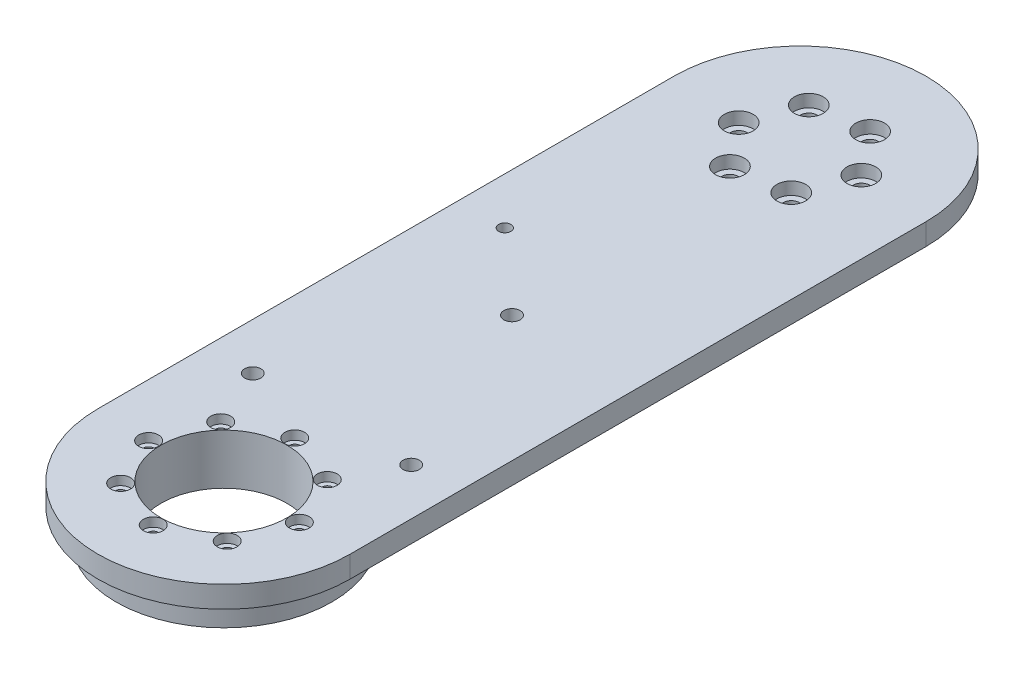
SolidWorks part; units mm, degrees
material "Aleación 6061"
ref_plane "Alzado" through (0, 0, 0) normal (0, 0, 1) x (1, 0, 0)
ref_plane "Planta" through (0, 0, 0) normal (0, 1, 0) x (1, 0, 0)
ref_plane "Vista lateral" through (0, 0, 0) normal (1, 0, 0) x (0, 0, -1)
sketch "Sk_Placa" plane through (0, 0, 0) normal (0, 1, 0) x (1, 0, 0)
  line L1 (-35, -330) -> (35, -330)
  line L2 (-35, -330) -> (-35, -170)
  line L3 (-35, -170) -> (35, -170)
  line L4 (35, -330) -> (35, -170)
  line L5 (-35, -330) -> (35, -170) construction
  line L6 (-35, -170) -> (35, -330) construction
  point P0 (0, -250)
  dimension "D1" = 70
  dimension "D2" = 160
  dimension "D3" = 250
extrude "Placa" add sketch "Sk_Placa" along normal blind 6 from offset 46.75
sketch "Sk_Extremos" plane through (0, 0, 0) normal (0, 1, 0) x (1, 0, 0)
  circle A0 centre (0, -170) radius 35
  circle A1 centre (0, -330) radius 35
  dimension "D1" = 70
  dimension "D3" = 70
  dimension "D2" = 170
  dimension "D4" = 330
extrude "Extremos" add sketch "Sk_Extremos" along normal blind 6 from offset 46.75
sketch "Sk_Pasantes_M4_separadores" plane through (0, 0, 0) normal (0, 1, 0) x (1, 0, 0)
  circle A0 centre (0, -250) radius 2.25
  circle A1 centre (-22, -300) radius 2.25
  circle A2 centre (22, -300) radius 2.25
  dimension "D1" = 4.5
  dimension "D3" = 4.5
  dimension "D6" = 4.5
  dimension "D2" = 250
  dimension "D4" = 22
  dimension "D5" = 300
  dimension "D7" = 22
  dimension "D8" = 300
extrude "Pasantes_M4_separadores" cut sketch "Sk_Pasantes_M4_separadores" along normal blind 6 from offset 46.75
sketch "Sk_Asiento_J3" plane through (0, 0, 0) normal (0, 1, 0) x (1, 0, 0)
  circle A0 centre (0, -330) radius 30
  circle A1 centre (0, -330) radius 17.5
  dimension "D1" = 60
  dimension "D3" = 35
  dimension "D2" = 330
  dimension "D4" = 330
extrude "Asiento_J3" add sketch "Sk_Asiento_J3" along normal blind 8 from offset 38.75
sketch "Sk_Paso_rotor_J3" plane through (0, 0, 0) normal (0, 1, 0) x (1, 0, 0)
  circle A0 centre (0, -330) radius 17.5
  dimension "D1" = 35
  dimension "D2" = 330
extrude "Paso_rotor_J3" cut sketch "Sk_Paso_rotor_J3" along normal blind 14 from offset 38.75
sketch "Sk_Pasantes_M2-5_estator_J3" plane through (0, 0, 0) normal (0, 1, 0) x (1, 0, 0)
  circle A0 centre (20.29, -329.3624) radius 1.45
  circle A1 centre (14.7981, -343.8963) radius 1.45
  circle A2 centre (0.6376, -350.29) radius 1.45
  circle A3 centre (-13.8963, -344.7981) radius 1.45
  circle A4 centre (-20.29, -330.6376) radius 1.45
  circle A5 centre (-14.7981, -316.1037) radius 1.45
  circle A6 centre (-0.6376, -309.71) radius 1.45
  circle A7 centre (13.8963, -315.2019) radius 1.45
  dimension "D1" = 2.9
  dimension "D4" = 2.9
  dimension "D7" = 2.9
  dimension "D10" = 2.9
  dimension "D13" = 2.9
  dimension "D16" = 2.9
  dimension "D19" = 2.9
  dimension "D22" = 2.9
  dimension "D2" = 20.29
  dimension "D3" = 329.3624
  dimension "D5" = 14.7981
  dimension "D6" = 343.8963
  dimension "D8" = 0.6376
  dimension "D9" = 350.29
  dimension "D11" = 13.8963
  dimension "D12" = 344.7981
  dimension "D14" = 20.29
  dimension "D15" = 330.6376
  dimension "D17" = 14.7981
  dimension "D18" = 316.1037
  dimension "D20" = 0.6376
  dimension "D21" = 309.71
  dimension "D23" = 13.8963
  dimension "D24" = 315.2019
extrude "Pasantes_M2-5_estator_J3" cut sketch "Sk_Pasantes_M2-5_estator_J3" along normal blind 14 from offset 38.75
sketch "Sk_Cajas_M2-5_J3" plane through (0, 0, 0) normal (0, 1, 0) x (1, 0, 0)
  circle A0 centre (20.29, -329.3624) radius 2.75
  circle A1 centre (14.7981, -343.8963) radius 2.75
  circle A2 centre (0.6376, -350.29) radius 2.75
  circle A3 centre (-13.8963, -344.7981) radius 2.75
  circle A4 centre (-20.29, -330.6376) radius 2.75
  circle A5 centre (-14.7981, -316.1037) radius 2.75
  circle A6 centre (-0.6376, -309.71) radius 2.75
  circle A7 centre (13.8963, -315.2019) radius 2.75
  dimension "D1" = 5.5
  dimension "D4" = 5.5
  dimension "D7" = 5.5
  dimension "D10" = 5.5
  dimension "D13" = 5.5
  dimension "D16" = 5.5
  dimension "D19" = 5.5
  dimension "D22" = 5.5
  dimension "D2" = 20.29
  dimension "D3" = 329.3624
  dimension "D5" = 14.7981
  dimension "D6" = 343.8963
  dimension "D8" = 0.6376
  dimension "D9" = 350.29
  dimension "D11" = 13.8963
  dimension "D12" = 344.7981
  dimension "D14" = 20.29
  dimension "D15" = 330.6376
  dimension "D17" = 14.7981
  dimension "D18" = 316.1037
  dimension "D20" = 0.6376
  dimension "D21" = 309.71
  dimension "D23" = 13.8963
  dimension "D24" = 315.2019
extrude "Cajas_M2-5_J3" cut sketch "Sk_Cajas_M2-5_J3" along normal blind 2.5 from offset 50.25
sketch "Sk_Pasantes_M4_salida_J2" plane through (0, 0, 0) normal (0, 1, 0) x (1, 0, 0)
  circle A0 centre (14.8391, -167.8088) radius 2.25
  circle A1 centre (9.3172, -181.7554) radius 2.25
  circle A2 centre (-5.5219, -183.9466) radius 2.25
  circle A3 centre (-14.8391, -172.1912) radius 2.25
  circle A4 centre (-9.3172, -158.2446) radius 2.25
  circle A5 centre (5.5219, -156.0534) radius 2.25
  dimension "D1" = 4.5
  dimension "D4" = 4.5
  dimension "D7" = 4.5
  dimension "D10" = 4.5
  dimension "D13" = 4.5
  dimension "D16" = 4.5
  dimension "D2" = 14.8391
  dimension "D3" = 167.8088
  dimension "D5" = 9.3172
  dimension "D6" = 181.7554
  dimension "D8" = 5.5219
  dimension "D9" = 183.9466
  dimension "D11" = 14.8391
  dimension "D12" = 172.1912
  dimension "D14" = 9.3172
  dimension "D15" = 158.2446
  dimension "D17" = 5.5219
  dimension "D18" = 156.0534
extrude "Pasantes_M4_salida_J2" cut sketch "Sk_Pasantes_M4_salida_J2" along normal blind 6 from offset 46.75
sketch "Sk_Cajas_M4_J2" plane through (0, 0, 0) normal (0, 1, 0) x (1, 0, 0)
  circle A0 centre (14.8391, -167.8088) radius 4
  circle A1 centre (9.3172, -181.7554) radius 4
  circle A2 centre (-5.5219, -183.9466) radius 4
  circle A3 centre (-14.8391, -172.1912) radius 4
  circle A4 centre (-9.3172, -158.2446) radius 4
  circle A5 centre (5.5219, -156.0534) radius 4
  dimension "D1" = 8
  dimension "D4" = 8
  dimension "D7" = 8
  dimension "D10" = 8
  dimension "D13" = 8
  dimension "D16" = 8
  dimension "D2" = 14.8391
  dimension "D3" = 167.8088
  dimension "D5" = 9.3172
  dimension "D6" = 181.7554
  dimension "D8" = 5.5219
  dimension "D9" = 183.9466
  dimension "D11" = 14.8391
  dimension "D12" = 172.1912
  dimension "D14" = 9.3172
  dimension "D15" = 158.2446
  dimension "D17" = 5.5219
  dimension "D18" = 156.0534
extrude "Cajas_M4_J2" cut sketch "Sk_Cajas_M4_J2" along normal blind 3.5 from offset 49.25
sketch "Sk_Pasante_M3_cincho" plane through (0, 0, 0) normal (0, 1, 0) x (1, 0, 0)
  circle A0 centre (-22, -230) radius 1.7
  dimension "D1" = 3.4
  dimension "D2" = 22
  dimension "D3" = 230
extrude "Pasante_M3_cincho" cut sketch "Sk_Pasante_M3_cincho" along normal blind 6 from offset 46.75
